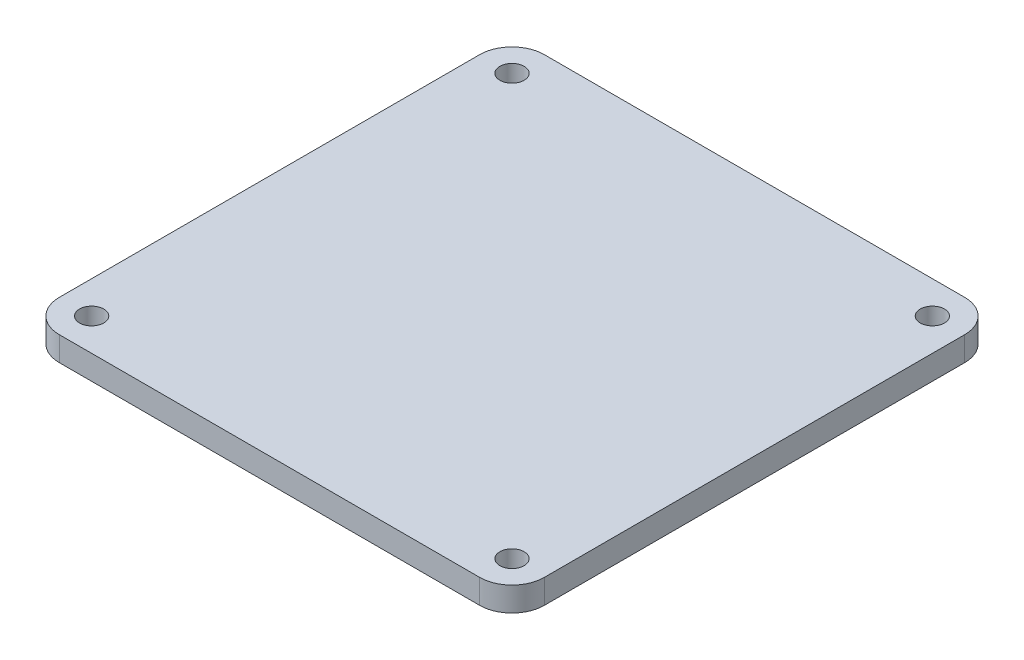
SolidWorks part; units mm, degrees
ref_plane "前视基准面" through (0, 0, 0) normal (0, 0, 1) x (1, 0, 0)
ref_plane "上视基准面" through (0, 0, 0) normal (0, 1, 0) x (1, 0, 0)
ref_plane "右视基准面" through (0, 0, 0) normal (1, 0, 0) x (0, 0, -1)
sketch "草图1" plane through (0, 0, 0) normal (0, 1, 0) x (1, 0, 0)
  line L1 (-26, -30) -> (26, -30)
  line L2 (-30, -26) -> (-30, 26)
  line L3 (-26, 30) -> (26, 30)
  line L4 (30, -26) -> (30, 26)
  line L7 (-26, -26) -> (26, -26) construction
  line L8 (-26, -26) -> (-26, 26) construction
  line L9 (-26, 26) -> (26, 26) construction
  line L10 (26, -26) -> (26, 26) construction
  circle A0 centre (-26, 26) radius 1.5
  circle A1 centre (26, 26) radius 1.5
  circle A2 centre (26, -26) radius 1.5
  circle A3 centre (-26, -26) radius 1.5
  arc A4 (-26, -30) -> (-30, -26) centre (-26, -26) cw
  arc A5 (26, -30) -> (30, -26) centre (26, -26) ccw
  arc A6 (26, 30) -> (30, 26) centre (26, 26) cw
  arc A7 (-30, 26) -> (-26, 30) centre (-26, 26) cw
  point P0 (0, 0)
  point P5 (0, 0)
  point P14 (-30, -30)
  point P21 (0, 0)
  point P28 (-30, 30)
  dimension "D3" = 3
  dimension "D5" = 4
  dimension "D1" = 60
  dimension "D2" = 52
  dimension "D4" = 4
extrude "凸台-拉伸1" add sketch "草图1" along normal blind 3
